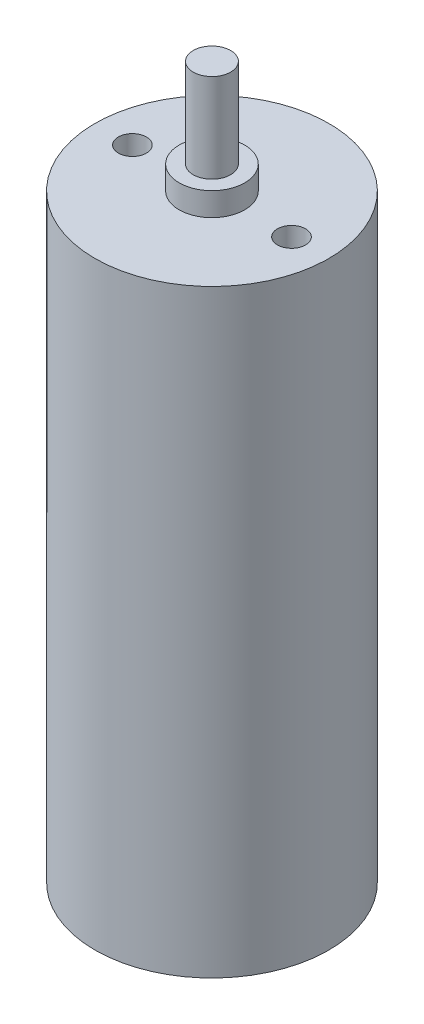
SolidWorks part; units mm, degrees
material "ABS"
ref_plane "Alzado" through (0, 0, 0) normal (0, 0, 1) x (1, 0, 0)
ref_plane "Planta" through (0, 0, 0) normal (0, 1, 0) x (1, 0, 0)
ref_plane "Vista lateral" through (0, 0, 0) normal (1, 0, 0) x (0, 0, -1)
sketch "Croquis1" plane through (0, 0, 0) normal (0, 1, 0) x (1, 0, 0)
  circle A0 centre (0, 0) radius 12.5
  dimension "D1" = 25
extrude "Saliente-Extruir1" add sketch "Croquis1" along normal blind 64
sketch "Croquis2" plane through (0, 64, 0) normal (0, 1, 0) x (1, 0, 0)
  line L0 (-8.5, 0) -> (8.5, 0)
  circle A0 centre (-8.5, 0) radius 1.5
  circle A1 centre (8.5, 0) radius 1.5
  point P4 (0, 0)
  dimension "D2" = 3
  dimension "D3" = 3
  dimension "D1" = 17
extrude "Cortar-Extruir1" cut sketch "Croquis2" against normal blind 40
sketch "Croquis3" plane through (0, 64, 0) normal (0, 1, 0) x (1, 0, 0)
  circle A0 centre (0, 0) radius 3.5
  dimension "D1" = 7
extrude "Saliente-Extruir2" add sketch "Croquis3" along normal blind 2.5
sketch "Croquis4" plane through (0, 66.5, 0) normal (0, 1, 0) x (1, 0, 0)
  circle A0 centre (0, 0) radius 2
  dimension "D1" = 4
extrude "Saliente-Extruir3" add sketch "Croquis4" along normal blind 9.5
